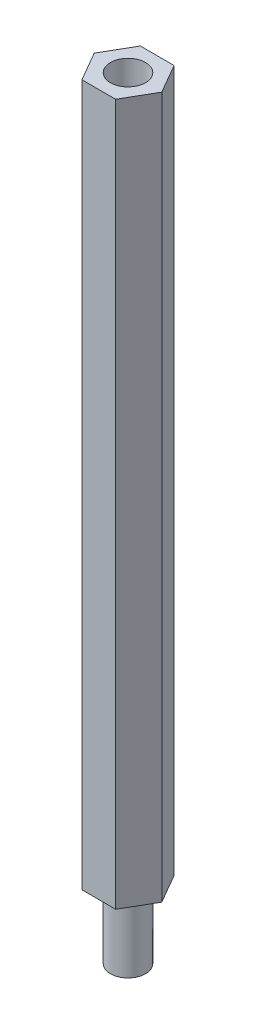
SolidWorks part; units mm, degrees
material "ABS"
ref_plane "Alzado" through (0, 0, 0) normal (0, 0, 1) x (1, 0, 0)
ref_plane "Planta" through (0, 0, 0) normal (0, 1, 0) x (1, 0, 0)
ref_plane "Vista lateral" through (0, 0, 0) normal (1, 0, 0) x (0, 0, -1)
sketch "Croquis1" plane through (0, 0, 0) normal (0, 1, 0) x (1, 0, 0)
  line L1 (1.4434, -2.5) -> (2.8868, 0)
  line L2 (2.8868, 0) -> (1.4434, 2.5)
  line L3 (1.4434, 2.5) -> (-1.4434, 2.5)
  line L4 (-1.4434, 2.5) -> (-2.8868, 0)
  line L5 (-2.8868, 0) -> (-1.4434, -2.5)
  line L6 (-1.4434, -2.5) -> (1.4434, -2.5)
  circle A0 centre (0, 0) radius 2.5 construction
  circle A1 centre (0, 0) radius 1.5
  dimension "D2" = 3
  dimension "D1" = 5
extrude "Saliente-Extruir1" add sketch "Croquis1" along normal blind 60
sketch "Croquis2" plane through (0, 0, 0) normal (0, -1, 0) x (1, 0, 0)
  circle A0 centre (0, 0) radius 1.5 construction
  circle A1 centre (0, 0) radius 1.5
extrude "Saliente-Extruir2" add sketch "Croquis2" along normal blind 6 separate body
